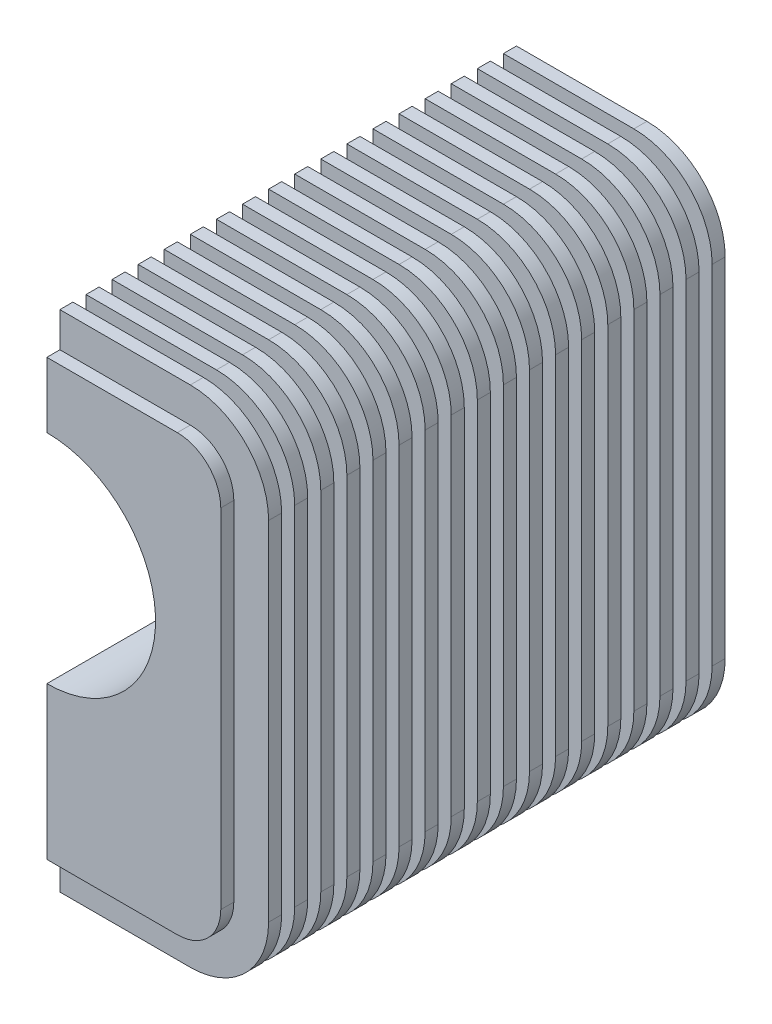
SolidWorks part; units mm, degrees
ref_plane "Płaszczyzna przednia" through (0, 0, 0) normal (0, 0, 1) x (1, 0, 0)
ref_plane "Płaszczyzna górna" through (0, 0, 0) normal (0, 1, 0) x (1, 0, 0)
ref_plane "Płaszczyzna prawa" through (0, 0, 0) normal (1, 0, 0) x (0, 0, -1)
sketch "Szkic1" plane through (0, 0, 0) normal (0, 0, 1) x (1, 0, 0)
  line L0 (0, -95) -> (30, -95) construction
  line L1 (40, -5) -> (40, -85) construction
  line L2 (0, 5) -> (30, 5) construction
  line L3 (0, -95) -> (30, -95)
  line L4 (40, -5) -> (40, -85)
  line L5 (0, 5) -> (30, 5)
  line L6 (0, 5) -> (0, -95)
  arc A0 (30, -95) -> (40, -85) centre (30, -85) ccw construction
  arc A1 (40, -5) -> (30, 5) centre (30, -5) ccw construction
  arc A2 (30, -95) -> (40, -85) centre (30, -85) ccw
  arc A3 (40, -5) -> (30, 5) centre (30, -5) ccw
extrude "Dodanie-wyciągnięcie1" add sketch "Szkic1" along normal blind 108
sketch "Szkic2" plane through (0, 0, 108) normal (0, 0, 1) x (1, 0, 0)
  circle A0 centre (0, -35) radius 25 construction
  circle A1 centre (0, -35) radius 25
extrude "Wytnij-wyciągnięcie1" cut sketch "Szkic2" against normal through all
sketch "Szkic4" plane through (0, 0, 0) normal (0, 0, -1) x (-1, 0, 0)
  line L0 (0, -95) -> (-30, -95) construction
  line L1 (-30, 5) -> (0, 5) construction
  line L2 (-40, -85) -> (-40, -5) construction
  line L3 (0, -95) -> (-30, -95)
  line L4 (-30, 5) -> (0, 5)
  line L5 (-40, -85) -> (-40, -5)
  line L6 (0, -103) -> (-30, -103)
  line L7 (-48, -85) -> (-48, -5)
  line L8 (-30, 13) -> (0, 13)
  line L9 (0, 13) -> (0, 5)
  line L10 (0, -95) -> (0, -103)
  arc A0 (-40, -85) -> (-30, -95) centre (-30, -85) ccw construction
  arc A1 (-30, 5) -> (-40, -5) centre (-30, -5) ccw construction
  arc A2 (-40, -85) -> (-30, -95) centre (-30, -85) ccw
  arc A3 (-30, 5) -> (-40, -5) centre (-30, -5) ccw
  arc A4 (-48, -85) -> (-30, -103) centre (-30, -85) ccw
  arc A5 (-30, 13) -> (-48, -5) centre (-30, -5) ccw
  dimension "D1" = 8
extrude "Dodanie-wyciągnięcie2" add sketch "Szkic4" against normal blind 3 contours L10 L6 A4 L7 A5 L8 L9 L4 A3 L5 A2 L3
pattern_linear "Szyk liniowy1" count 18 spacing 6 along (0, 0, 1) of "Dodanie-wyciągnięcie2"
